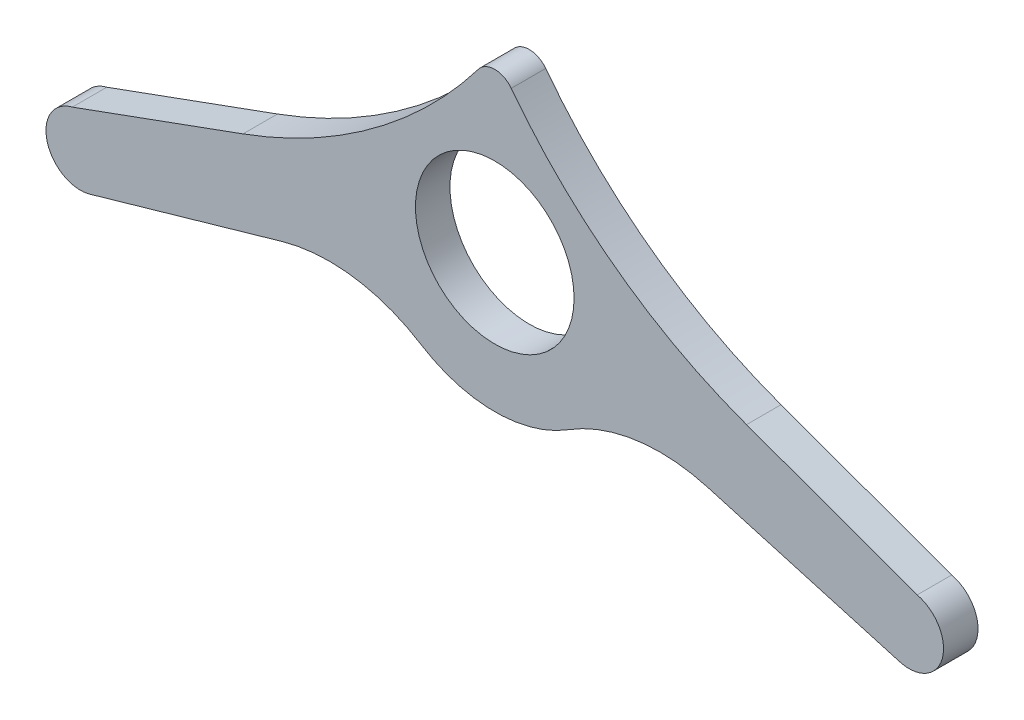
SolidWorks part; units mm, degrees
ref_plane "Front Plane" through (0, 0, 0) normal (0, 0, 1) x (1, 0, 0)
ref_plane "Top Plane" through (0, 0, 0) normal (0, 1, 0) x (1, 0, 0)
ref_plane "Right Plane" through (0, 0, 0) normal (1, 0, 0) x (0, 0, -1)
sketch "Sketch1" plane through (0, 0, 0) normal (0, 0, 1) x (1, 0, 0)
  line L0 (0, -55) -> (0, 55) construction
  line L1 (58.5095, -21.9747) -> (30.8681, -14.0486)
  line L2 (0, 0) -> (60.0789, -17.2273) construction
  line L3 (0, 0) -> (-60.0789, -17.2273) construction
  line L4 (55, 0) -> (-55, 0) construction
  line L5 (61.2637, -12.3697) -> (36.5095, -3.36)
  line L6 (-61.2637, -12.3697) -> (-36.5095, -3.36)
  line L7 (-58.5095, -21.9747) -> (-30.8681, -14.0486)
  circle A0 centre (0, 0) radius 11.5
  arc A1 (-10.6565, -16.9245) -> (10.6565, -16.9245) centre (0, 0) ccw
  circle A2 centre (0, 0) radius 62.5 construction
  arc A3 (-36.5095, -3.36) -> (-2.3908, 21.8122) centre (-62.161, 67.117) ccw
  arc A4 (30.8681, -14.0486) -> (10.6565, -16.9245) centre (23.9771, -38.0801) ccw
  arc A5 (61.2637, -12.3697) -> (58.5095, -21.9747) centre (60.0789, -17.2273) cw
  arc A6 (36.5095, -3.36) -> (2.3908, 21.8122) centre (62.161, 67.117) cw
  arc A7 (2.3908, 21.8122) -> (-2.3908, 21.8122) centre (0, 20) ccw
  arc A8 (-61.2637, -12.3697) -> (-58.5095, -21.9747) centre (-60.0789, -17.2273) ccw
  arc A9 (-30.8681, -14.0486) -> (-10.6565, -16.9245) centre (-23.9771, -38.0801) cw
  point P3 (0, 0)
  point P23 (0, 0)
  point P25 (0, 0)
  dimension "D1" = 23
  dimension "D2" = 40
  dimension "D3" = 125
  dimension "D6" = 25
  dimension "D8" = 5
  dimension "D10" = 6
  dimension "D11" = 75
  dimension "D5" = 16
  dimension "D9" = 4
extrude "Boss-Extrude1" add sketch "Sketch1" along normal blind 5
